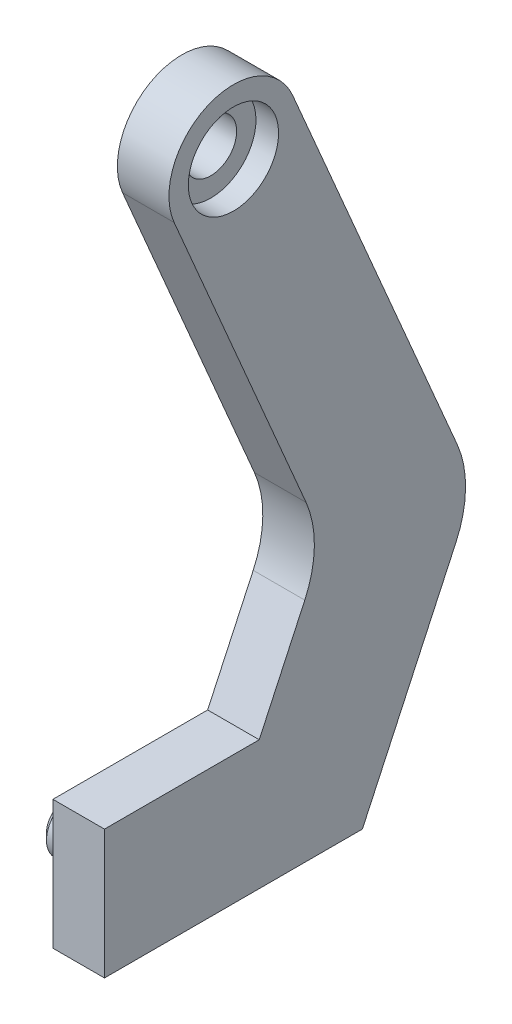
SolidWorks part; units mm, degrees
material "ABS"
ref_plane "Front Plane" through (0, 0, 0) normal (0, 0, 1) x (1, 0, 0)
ref_plane "Top Plane" through (0, 0, 0) normal (0, 1, 0) x (1, 0, 0)
ref_plane "Right Plane" through (0, 0, 0) normal (1, 0, 0) x (0, 0, -1)
sketch "Sketch1" plane through (0, 0, 0) normal (0, 0, 1) x (1, 0, 0)
  line L0 (0, 0) -> (0, -174.625)
  line L1 (0, -174.625) -> (171.45, -174.625)
  line L2 (171.45, -174.625) -> (171.45, 0)
  line L3 (171.45, 0) -> (158.75, 0)
  line L4 (158.75, 0) -> (158.75, -142.875)
  line L5 (158.75, -142.875) -> (12.7, -142.875)
  line L6 (12.7, -142.875) -> (12.7, 0)
  line L7 (12.7, 0) -> (0, 0)
  dimension "D1" = 171.45
  dimension "D2" = 12.7
  dimension "D3" = 31.75
  dimension "D4" = 174.625
extrude "Boss-Extrude1" add sketch "Sketch1" along normal blind 88.9
sketch "Sketch2" plane through (0, -142.875, 0) normal (0, 1, 0) x (1, 0, 0)
  line L0 (158.75, -88.9) -> (158.75, 0) construction
  line L1 (12.7, 0) -> (158.75, 0)
  line L2 (12.7, 0) -> (12.7, -25.4)
  line L3 (12.7, -25.4) -> (158.75, -25.4)
  line L4 (158.75, 0) -> (158.75, -25.4)
  line L5 (158.75, -88.9) -> (12.7, -88.9) construction
  line L6 (0, -50.8) -> (71.8503, -85.7079)
  line L9 (85.725, 0) -> (85.725, -57.15) construction
  line L10 (171.45, -50.8) -> (99.5997, -85.7079)
  line L12 (0, -50.8) -> (171.45, -50.8) construction
  line L13 (171.45, -50.8) -> (171.45, -88.9)
  line L14 (171.45, -88.9) -> (0, -88.9)
  line L15 (0, -88.9) -> (0, -50.8)
  circle A0 centre (85.725, -57.15) radius 31.75
  line M10 (158.75, 0) -> (12.7, 0)
  line M11 (12.7, 0) -> (12.7, -88.9)
  line M13 (158.75, -88.9) -> (158.75, 0)
  dimension "D3" = 63.5
  dimension "D1" = 63.5
  dimension "D2" = 38.1
extrude "Cut-Extrude2" cut sketch "Sketch2" against normal through all both and the other way through all contours L3 M11 M13 M10
sketch "Sketch3" plane through (0, -174.625, 0) normal (0, -1, 0) x (1, 0, 0)
  circle A2 centre (85.725, 57.15) radius 28.575
  dimension "D1" = 57.15
extrude "Cut-Extrude5" cut sketch "Sketch3" against normal offset from surface (28.575 mm away) 3.175 up to face at (85.725, -142.875, 57.15)
sketch "Sketch4" plane through (0, -146.05, 0) normal (0, -1, 0) x (1, 0, 0)
  circle A0 centre (85.725, 57.15) radius 28.575 construction
  circle A1 centre (85.725, 57.15) radius 28.575 construction
  circle A2 centre (85.725, 57.15) radius 12.7
  dimension "D1" = 25.4
extrude "Cut-Extrude6" cut sketch "Sketch4" against normal through all both and the other way through all
sketch "Sketch5" plane through (171.45, 0, 0) normal (1, 0, 0) x (0, 0, -1)
  line L0 (-88.9, 0) -> (0, 0) construction
  line L1 (-44.45, -142.875) -> (-69.85, -142.875) construction
  line L2 (-44.45, -142.875) -> (-69.85, -142.875) construction
  line L3 (-57.15, -142.875) -> (-57.15, 0) construction
  line L4 (-71.7453, -22.1194) -> (-39.2695, -98.0259)
  line L5 (-42.5547, -9.6306) -> (-2.0475, -104.3089)
  line L6 (-50.8, -142.875) -> (-39.5832, -118.7117)
  line L8 (-88.9, -174.625) -> (-88.9, 0) construction
  line L9 (-25.4, -174.625) -> (-2.3613, -124.9947)
  line L11 (-50.8, -142.875) -> (-88.9, -142.875)
  line L12 (0, -174.625) -> (0, 0) construction
  line L13 (-88.9, -174.625) -> (0, -174.625) construction
  line L14 (-25.4, -174.625) -> (0, -174.625)
  line L15 (0, -174.625) -> (0, 0)
  line L16 (0, 0) -> (-88.9, 0)
  line L17 (-88.9, 0) -> (-88.9, -142.875)
  line L18 (-25.4, -174.625) -> (-25.4, -142.875) construction
  line L19 (-25.4, -174.625) -> (-25.4, -142.875) construction
  circle A0 centre (-57.15, -15.875) radius 15.875
  arc A3 (-2.3613, -124.9947) -> (-2.0475, -104.3089) centre (-25.4, -114.3) ccw
  arc A5 (-39.5832, -118.7117) -> (-39.2695, -98.0259) centre (-62.622, -108.017) ccw
  dimension "D1" = 31.75
  dimension "D2" = 25.4
  dimension "D4" = 25.4
  dimension "D5" = 34.858
  dimension "D3" = 60.325
  dimension "D6" = 38.1
extrude "Cut-Extrude7" cut sketch "Sketch5" against normal through all both and the other way through all
sketch "Sketch6" plane through (171.45, 0, 0) normal (1, 0, 0) x (0, 0, -1)
  circle A2 centre (-57.15, -15.875) radius 6.35
  dimension "D2" = 12.7
extrude "Cut-Extrude8" cut sketch "Sketch6" against normal up to surface (12.7 mm away) and the other way through all up to face at (158.75, -102.6264, 33.4448)
sketch "Sketch7" plane through (12.7, 0, 0) normal (1, 0, 0) x (0, 0, -1)
  circle A2 centre (-57.15, -15.875) radius 6.35
  arc A3 (-42.5547, -9.6306) -> (-71.7453, -22.1194) centre (-57.15, -15.875) ccw construction
  dimension "D1" = 12.7
extrude "Cut-Extrude9" cut sketch "Sketch7" against normal up to surface (12.7 mm away) up to face at (0, -109.8263, 45.3403)
sketch "Sketch12" plane through (12.7, 0, 0) normal (1, 0, 0) x (0, 0, -1)
  circle A0 centre (-57.15, -15.875) radius 12.7
  dimension "D1" = 25.4
extrude "Cut-Extrude13" cut sketch "Sketch12" against normal blind 3.175
sketch "Sketch14" plane through (12.7, 0, 0) normal (1, 0, 0) x (0, 0, -1)
  circle A0 centre (-53.7708, -24.7804) radius 1.5875
  circle A1 centre (-66.5519, -14.3488) radius 1.5875
  circle A2 centre (-51.1273, -8.4958) radius 1.5875
extrude "Cut-Extrude14" cut sketch "Sketch14" along normal up to surface (146.05 mm away) and the other way through all from surface at -12.7 starting at face at (0, -9.525, 57.15)
sketch "Sketch15" plane through (0, 0, 88.9) normal (0, 0, 1) x (1, 0, 0)
  line L1 (0, -174.625) -> (158.75, -174.625)
  line L2 (0, -174.625) -> (0, 0)
  line L3 (0, 0) -> (158.75, 0)
  line L4 (158.75, -174.625) -> (158.75, 0)
  line L6 (0, -174.625) -> (171.45, -174.625) construction
  line L7 (171.45, 0) -> (158.75, 0) construction
  line L8 (0, -142.875) -> (0, -174.625) construction
  line L9 (158.75, -22.1194) -> (158.75, -98.0259) construction
extrude "Cut-Extrude15" cut sketch "Sketch15" against normal through all both and the other way through all
sketch "Sketch17" plane through (158.75, 0, 0) normal (-1, 0, 0) x (0, 0, 1)
  line L0 (88.9, -174.625) -> (88.9, -142.875) construction
  line L1 (25.4, -174.625) -> (88.9, -174.625) construction
  circle A0 centre (76.2, -158.75) radius 6.35
  circle A1 centre (38.1, -158.75) radius 6.35
  dimension "D4" = 12.7
  dimension "D1" = 38.1
  dimension "D2" = 12.7
  dimension "D3" = 15.875
extrude "Boss-Extrude3" add sketch "Sketch17" along normal blind 9.525
chamfer "Chamfer2" distance 1.5875 angle 45 2 edges at (149.225, -165.1, 38.1) (149.225, -165.1, 76.2)
sketch "Sketch18" plane through (171.45, 0, 0) normal (1, 0, 0) x (0, 0, -1)
  circle A0 centre (-57.15, -15.875) radius 11.1125
  dimension "D1" = 22.225
extrude "Cut-Extrude16" cut sketch "Sketch18" against normal blind 5.5626 and the other way through all
